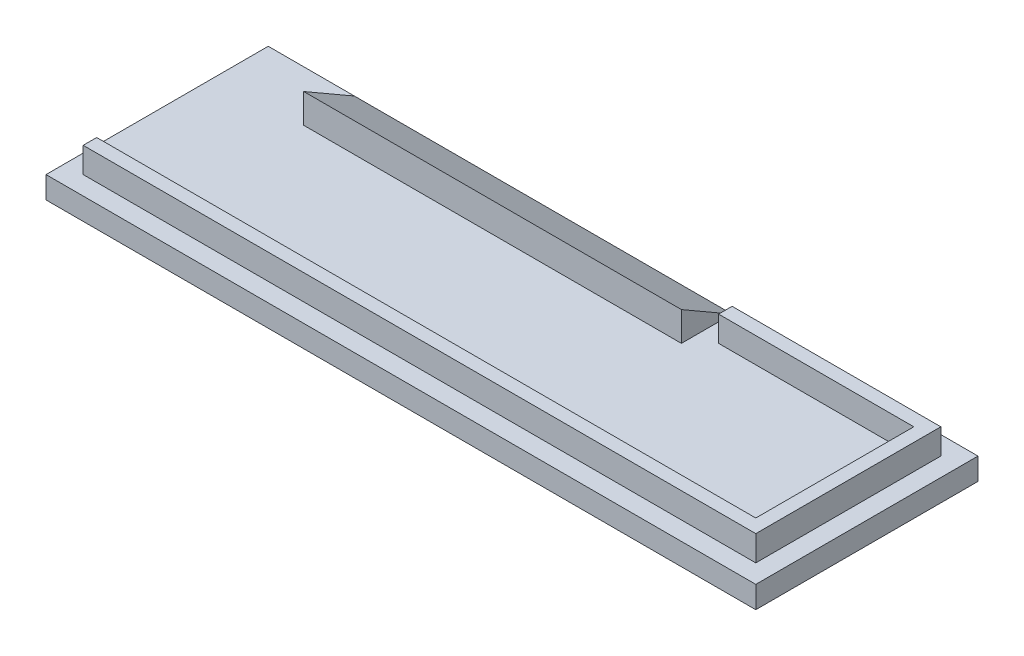
SolidWorks part; units mm, degrees
ref_plane "Front Plane" through (0, 0, 0) normal (0, 0, 1) x (1, 0, 0)
ref_plane "Top Plane" through (0, 0, 0) normal (0, 1, 0) x (1, 0, 0)
ref_plane "Right Plane" through (0, 0, 0) normal (1, 0, 0) x (0, 0, -1)
sketch "Sketch1" plane through (0, 0, 0) normal (0, 1, 0) x (1, 0, 0)
  line L1 (0, 0) -> (42, 0)
  line L2 (0, 0) -> (0, 13.15)
  line L3 (0, 13.15) -> (42, 13.15)
  line L4 (42, 0) -> (42, 13.15)
  dimension "D1" = 13.15
  dimension "D2" = 42
extrude "Boss-Extrude1" add sketch "Sketch1" along normal blind 1.3
sketch "Sketch3" plane through (0, 0, 0) normal (-1, 0, 0) x (0, 0, 1)
  line L0 (-13.15, 1.3) -> (-10.15, 1.3)
  line L1 (-13.15, 1.3) -> (0, 1.3) construction
  line L2 (-10.15, 1.3) -> (-10.15, 3.0321)
  line L3 (-10.15, 3.0321) -> (-13.15, 1.3)
  dimension "D1" = 3
  dimension "D2" = 30
extrude "Boss-Extrude3" add sketch "Sketch3" against normal blind 22.35 from offset 5.1 offset against normal yes
sketch "Sketch4" plane through (0, 1.3, 0) normal (0, 1, 0) x (1, 0, 0)
  line L0 (27.45, 10.15) -> (39, 10.15)
  line L1 (39, 10.15) -> (39, 3)
  line L2 (39, 3) -> (0, 3)
  line L3 (0, 13.15) -> (0, 0) construction
  line L4 (0, 0) -> (42, 0) construction
  line L5 (42, 0) -> (42, 13.15) construction
  line L6 (0, 3) -> (0, 0)
  line L7 (0, 0) -> (42, 0)
  line L8 (42, 0) -> (42, 13.15)
  line L9 (42, 13.15) -> (27.45, 13.15)
  line L10 (27.45, 13.15) -> (27.45, 10.15)
  line L11 (28.55, 12.05) -> (28.55, 11.25)
  line L12 (28.55, 11.25) -> (40.1, 11.25)
  line L13 (40.1, 11.25) -> (40.1, 1.9)
  line L14 (40.1, 1.9) -> (1.1, 1.9)
  line L15 (1.1, 1.9) -> (1.1, 1.1)
  line L16 (1.1, 1.1) -> (40.9, 1.1)
  line L17 (40.9, 1.1) -> (40.9, 12.05)
  line L18 (40.9, 12.05) -> (28.55, 12.05)
  dimension "D1" = 3
  dimension "D2" = 3
  dimension "D3" = 1.1
extrude "Boss-Extrude4" add sketch "Sketch4" along normal blind 1.5 contours L17 L18 L11 L12 L13 L14 L15 L16
